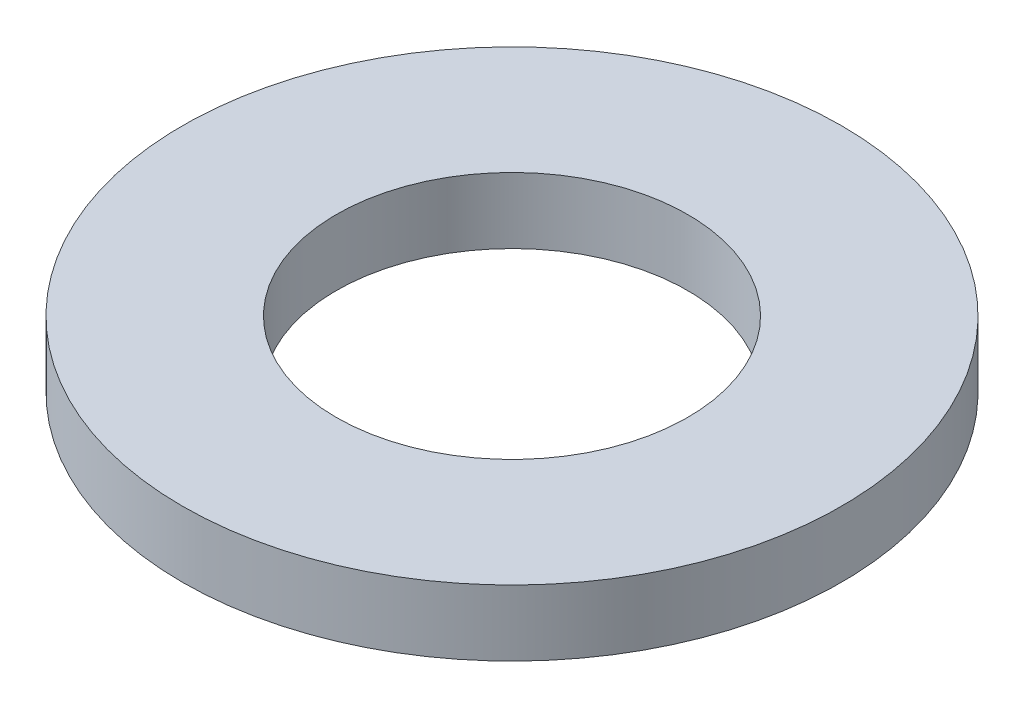
SolidWorks part; units mm, degrees
material "201 退火不锈钢 (SS)"
ref_plane "前视基准面" through (0, 0, 0) normal (0, 0, 1) x (1, 0, 0)
ref_plane "上视基准面" through (0, 0, 0) normal (0, 1, 0) x (1, 0, 0)
ref_plane "右视基准面" through (0, 0, 0) normal (1, 0, 0) x (0, 0, -1)
sketch "草图1" plane through (0, 0, 0) normal (0, 1, 0) x (1, 0, 0)
  circle A0 centre (0, 0) radius 4
  circle A1 centre (0, 0) radius 7.5
  dimension "D1" = 8
  dimension "D2" = 15
extrude "凸台-拉伸1" add sketch "草图1" along normal blind 1.5
